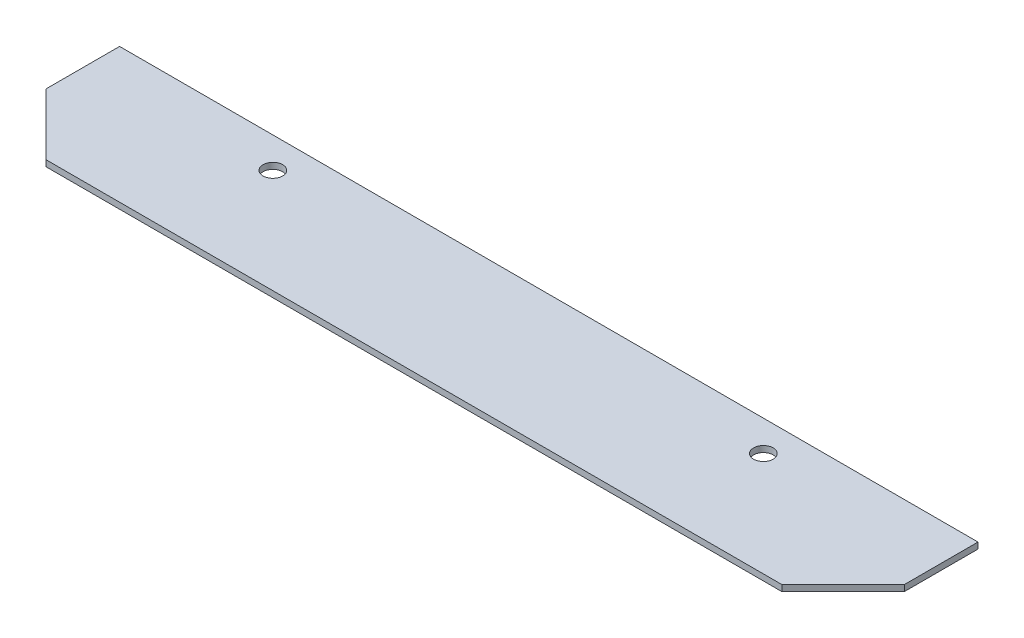
SolidWorks part; units mm, degrees
ref_plane "前视基准面" through (0, 0, 0) normal (0, 0, 1) x (1, 0, 0)
ref_plane "上视基准面" through (0, 0, 0) normal (0, 1, 0) x (1, 0, 0)
ref_plane "右视基准面" through (0, 0, 0) normal (1, 0, 0) x (0, 0, -1)
other "Configuration Table"
sketch "草图1" plane through (0, 0, 0) normal (0, 1, 0) x (1, 0, 0)
  line L1 (-70, 11) -> (70, 11)
  line L2 (-70, 11) -> (-70, -11)
  line L3 (-70, -11) -> (70, -11)
  line L4 (70, 11) -> (70, -11)
  line L5 (-70, 11) -> (70, -11) construction
  line L6 (-70, -11) -> (70, 11) construction
  point P0 (0, 0)
  dimension "D1" = 22
  dimension "D2" = 140
extrude "凸台-拉伸1" add sketch "草图1" along normal blind 1
sketch "草图2" plane through (0, 0, 0) normal (0, -1, 0) x (1, 0, 0)
  line L0 (40, -6) -> (-40, -6) construction
  line L1 (0, -6) -> (0, 0) construction
  line L2 (0, -6) -> (0, -11) construction
  line L3 (70, -11) -> (-70, -11) construction
  circle A0 centre (40, -6) radius 1.6
  circle A1 centre (-40, -6) radius 1.6
  dimension "D2" = 3.2
  dimension "D1" = 5
  dimension "D3" = 80
extrude "切除-拉伸1" cut sketch "草图2" against normal blind 10
chamfer "倒角1" distance 10 angle 45 2 edges at (-70, 0.5, 11) (70, 0.5, 11)
